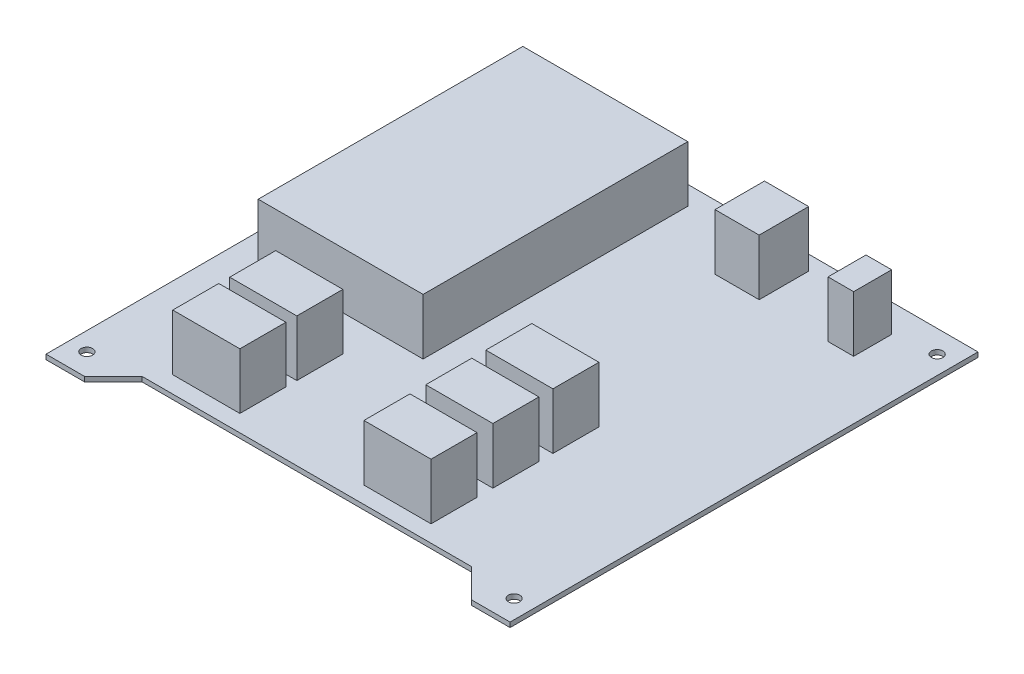
SolidWorks part; units mm, degrees
material "PPE"
ref_plane "Front" through (0, 0, 0) normal (0, 0, 1) x (1, 0, 0)
ref_plane "Top" through (0, 0, 0) normal (0, 1, 0) x (1, 0, 0)
ref_plane "Right" through (0, 0, 0) normal (1, 0, 0) x (0, 0, -1)
sketch "Sketch1" plane through (0, 0, 0) normal (0, 1, 0) x (1, 0, 0)
  line L0 (0, 0) -> (0, -77.47) construction
  line L1 (-76.835, 77.47) -> (76.835, 77.47)
  line L2 (-76.835, 77.47) -> (-76.835, -77.47)
  line L3 (-76.835, -77.47) -> (76.835, -77.47) construction
  line L4 (76.835, 77.47) -> (76.835, -77.47)
  line L5 (-76.835, 77.47) -> (76.835, -77.47) construction
  line L6 (-76.835, -77.47) -> (76.835, 77.47) construction
  line L7 (-76.835, -77.47) -> (-64.135, -77.47)
  line L8 (-64.135, -77.47) -> (-54.61, -67.945)
  line L9 (-54.61, -67.945) -> (54.61, -67.945)
  line L10 (76.835, -77.47) -> (64.135, -77.47)
  line L11 (64.135, -77.47) -> (54.61, -67.945)
  line L13 (-70.739, 70.0405) -> (70.739, 70.0405) construction
  line L14 (-70.739, 70.0405) -> (-70.739, -70.0405) construction
  line L15 (-70.739, -70.0405) -> (70.739, -70.0405) construction
  line L16 (70.739, 70.0405) -> (70.739, -70.0405) construction
  line L17 (-70.739, 70.0405) -> (70.739, -70.0405) construction
  line L18 (-70.739, -70.0405) -> (70.739, 70.0405) construction
  circle A0 centre (-70.739, 70.0405) radius 1.905
  circle A1 centre (-70.739, -70.0405) radius 1.905
  circle A2 centre (70.739, -70.0405) radius 1.905
  circle A3 centre (70.739, 70.0405) radius 1.905
  point P0 (0, 0)
  point P13 (0, -67.945)
  dimension "D8" = 3.81
  dimension "D1" = 153.67
  dimension "D2" = 154.94
  dimension "D3" = 9.525
  dimension "D4" = 12.7
  dimension "D5" = 9.525
  dimension "D6" = 141.478
  dimension "D7" = 140.081
extrude "Boss-Extrude1" add sketch "Sketch1" along normal blind 1.5875
sketch "Sketch2" plane through (0, 1.5875, 0) normal (0, 1, 0) x (1, 0, 0)
  line L1 (-49.9503, -47.1449) -> (-27.7253, -47.1449)
  line L2 (-49.9503, -47.1449) -> (-49.9503, -62.3849)
  line L3 (-49.9503, -62.3849) -> (-27.7253, -62.3849)
  line L4 (-27.7253, -47.1449) -> (-27.7253, -62.3849)
  line L5 (-49.9503, -47.1449) -> (-27.7253, -62.3849) construction
  line L6 (-49.9503, -62.3849) -> (-27.7253, -47.1449) construction
  line L7 (-49.9503, -28.2848) -> (-27.7253, -28.2848)
  line L8 (-49.9503, -28.2848) -> (-49.9503, -43.5248)
  line L9 (-49.9503, -43.5248) -> (-27.7253, -43.5248)
  line L10 (-27.7253, -28.2848) -> (-27.7253, -43.5248)
  line L11 (-49.9503, -28.2848) -> (-27.7253, -43.5248) construction
  line L12 (-49.9503, -43.5248) -> (-27.7253, -28.2848) construction
  line L13 (13.3574, -47.1449) -> (35.5824, -47.1449)
  line L14 (13.3574, -47.1449) -> (13.3574, -62.3849)
  line L15 (13.3574, -62.3849) -> (35.5824, -62.3849)
  line L16 (35.5824, -47.1449) -> (35.5824, -62.3849)
  line L17 (13.3574, -47.1449) -> (35.5824, -62.3849) construction
  line L18 (13.3574, -62.3849) -> (35.5824, -47.1449) construction
  line L19 (13.3574, -26.6766) -> (35.5824, -26.6766)
  line L20 (13.3574, -26.6766) -> (13.3574, -41.9166)
  line L21 (13.3574, -41.9166) -> (35.5824, -41.9166)
  line L22 (35.5824, -26.6766) -> (35.5824, -41.9166)
  line L23 (13.3574, -26.6766) -> (35.5824, -41.9166) construction
  line L24 (13.3574, -41.9166) -> (35.5824, -26.6766) construction
  line L25 (13.3574, -6.7932) -> (35.5824, -6.7932)
  line L26 (13.3574, -6.7932) -> (13.3574, -22.0332)
  line L27 (13.3574, -22.0332) -> (35.5824, -22.0332)
  line L28 (35.5824, -6.7932) -> (35.5824, -22.0332)
  line L29 (13.3574, -6.7932) -> (35.5824, -22.0332) construction
  line L30 (13.3574, -22.0332) -> (35.5824, -6.7932) construction
  line L31 (11.0182, 72.5769) -> (25.6384, 72.5769)
  line L32 (11.0182, 72.5769) -> (11.0182, 56.2023)
  line L33 (11.0182, 56.2023) -> (25.6384, 56.2023)
  line L34 (25.6384, 72.5769) -> (25.6384, 56.2023)
  line L35 (11.0182, 72.5769) -> (25.6384, 56.2023) construction
  line L36 (11.0182, 56.2023) -> (25.6384, 72.5769) construction
  line L37 (-67.5963, 71.1838) -> (-12.9863, 71.1838)
  line L38 (-67.5963, 71.1838) -> (-67.5963, -16.4462)
  line L39 (-67.5963, -16.4462) -> (-12.9863, -16.4462)
  line L40 (-12.9863, 71.1838) -> (-12.9863, -16.4462)
  line L41 (-67.5963, 71.1838) -> (-12.9863, -16.4462) construction
  line L42 (-67.5963, -16.4462) -> (-12.9863, 71.1838) construction
  line L43 (49.0307, 68.1908) -> (57.5104, 68.1908)
  line L44 (49.0307, 68.1908) -> (49.0307, 55.6175)
  line L45 (49.0307, 55.6175) -> (57.5104, 55.6175)
  line L46 (57.5104, 68.1908) -> (57.5104, 55.6175)
  line L47 (49.0307, 68.1908) -> (57.5104, 55.6175) construction
  line L48 (49.0307, 55.6175) -> (57.5104, 68.1908) construction
  point P0 (-38.8378, -54.7649)
  point P5 (-38.8378, -35.9048)
  point P10 (24.4699, -54.7649)
  point P15 (24.4699, -34.2966)
  point P20 (24.4699, -14.4132)
  point P25 (18.3283, 64.3896)
  point P30 (-40.2913, 27.3688)
  point P41 (53.2705, 61.9042)
  dimension "D1" = 22.225
  dimension "D2" = 15.24
  dimension "D3" = 54.61
  dimension "D4" = 87.63
extrude "Boss-Extrude2" add sketch "Sketch2" along normal blind 18.542
